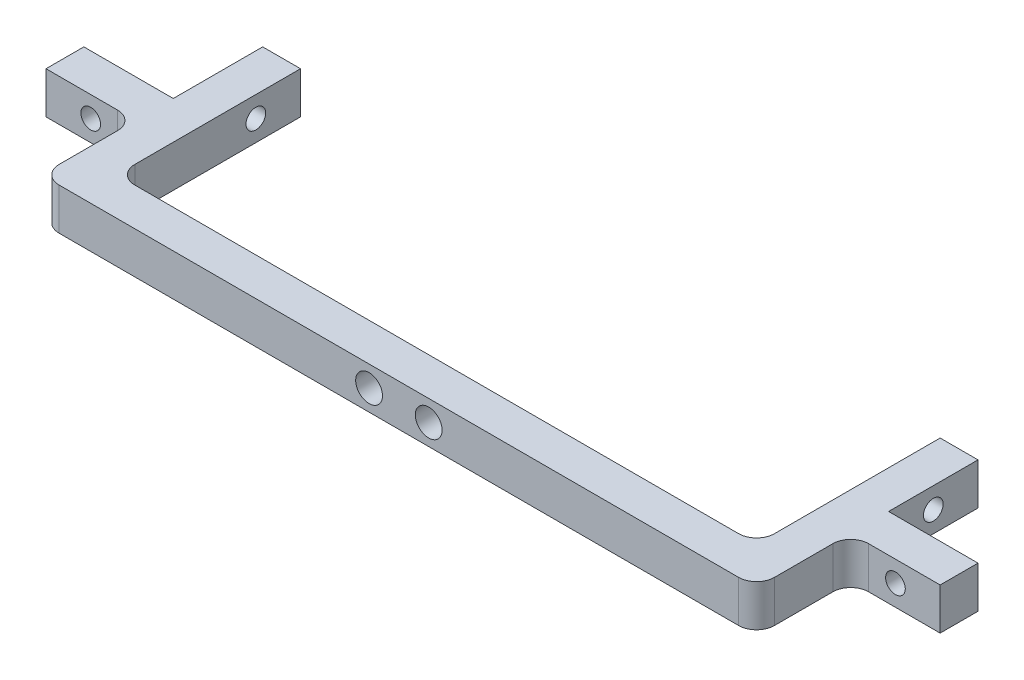
SolidWorks part; units mm, degrees
ref_plane "Front Plane" through (0, 0, 0) normal (0, 0, 1) x (1, 0, 0)
ref_plane "Top Plane" through (0, 0, 0) normal (0, 1, 0) x (1, 0, 0)
ref_plane "Right Plane" through (0, 0, 0) normal (1, 0, 0) x (0, 0, -1)
sketch "Sketch1" plane through (0, 0, 0) normal (0, 1, 0) x (1, 0, 0)
  line L0 (0, 0) -> (53.6504, 0)
  line L1 (53.6504, 0) -> (53.6504, 30.8)
  line L2 (53.6504, 30.8) -> (60.0004, 30.8)
  line L3 (60.0004, 30.8) -> (60.0004, 15.8)
  line L4 (60.0004, -6.35) -> (-59.9996, -6.35)
  line L6 (-60.0004, 30.8) -> (-53.6504, 30.8)
  line L7 (-53.6504, 30.8) -> (-53.6504, 0)
  line L8 (-53.6504, 0) -> (0, 0)
  line L9 (0, 52.9472) -> (0, -21.9318) construction
  line L10 (60.0004, 15.8) -> (75.0004, 15.8)
  line L12 (60.0004, 9.45) -> (75.0004, 9.45)
  line L13 (75.0004, 15.8) -> (75.0004, 9.45)
  line L14 (60.0004, 9.45) -> (60.0004, -6.35)
  line L15 (-75.0004, 15.8) -> (-75.0004, 9.45)
  line L16 (-60.0004, 9.45) -> (-75.0004, 9.45)
  line L17 (-60.0004, 15.8) -> (-75.0004, 15.8)
  line L18 (-60.0004, 30.8) -> (-60.0004, 15.8)
  line L19 (-60.0004, 9.45) -> (-59.9996, -6.35)
  line L21 (75.0009, 30.8) -> (-74.9991, 30.8) construction
  dimension "D1" = 120
  dimension "D2" = 6.35
  dimension "D4" = 6.35
  dimension "D5" = 15
  dimension "D6" = 6.35
  dimension "D7" = 15
  dimension "D10" = 53.6504
  dimension "D3" = 0
extrude "Boss-Extrude1" add sketch "Sketch1" along normal blind 7
sketch "Sketch2" plane through (60.0004, 0, 0) normal (1, 0, 0) x (0, 0, -1)
  line L0 (30.8, 7) -> (30.8, 0) construction
  circle A0 centre (23.3, 3.5) radius 1.65
  dimension "D1" = 3.3
  dimension "D2" = 7.5
extrude "Cut-Extrude1" cut sketch "Sketch2" against normal through all
sketch "Sketch3" plane through (0, 0, -15.8) normal (0, 0, -1) x (-1, 0, 0)
  line L0 (-75.0004, 3.5) -> (75.0004, 3.5) construction
  line L1 (-75.0004, 7) -> (-75.0004, 0) construction
  line L2 (75.0004, 7) -> (75.0004, 0) construction
  circle A0 centre (-67.5004, 3.5) radius 1.65
  circle A1 centre (67.5004, 3.5) radius 1.65
  dimension "D2" = 3.3
  dimension "D4" = 3.3
  dimension "D1" = 7.5
  dimension "D3" = 7.5
extrude "Cut-Extrude2" cut sketch "Sketch3" against normal up to surface (6.35 mm away) up to face at (-67.5004, 3.5, -9.45)
fillet "Fillet1" radius 3 6 edges at (60.0004, 3.5, -9.45) (53.6504, 3.5, 0) (60.0004, 3.5, 6.35) (-53.6504, 3.5, 0) (-59.9996, 3.5, 6.35) (-60.0004, 3.5, -9.45)
sketch "Sketch4" plane through (0, 0, 6.35) normal (0, 0, 1) x (1, 0, 0)
  line L0 (0.0003, 7) -> (0, 0) construction
  line L2 (-75.0004, 3.5) -> (75.0004, 3.5) construction
  line L3 (-75.0004, 7) -> (-75.0004, 0) construction
  line L4 (75.0004, 7) -> (75.0004, 0) construction
  line L5 (-56.9997, 7) -> (57.0004, 7) construction
  circle A0 centre (5.0002, 3.5) radius 2.25
  circle A2 centre (-4.9998, 3.5005) radius 2.25
  dimension "D1" = 4.5
  dimension "D2" = 5
extrude "Cut-Extrude3" cut sketch "Sketch4" against normal up to surface (6.35 mm away) up to face at (0, 3.5, 0)
equation "\"D6@Sketch1\"=\"D4@Sketch1\""
